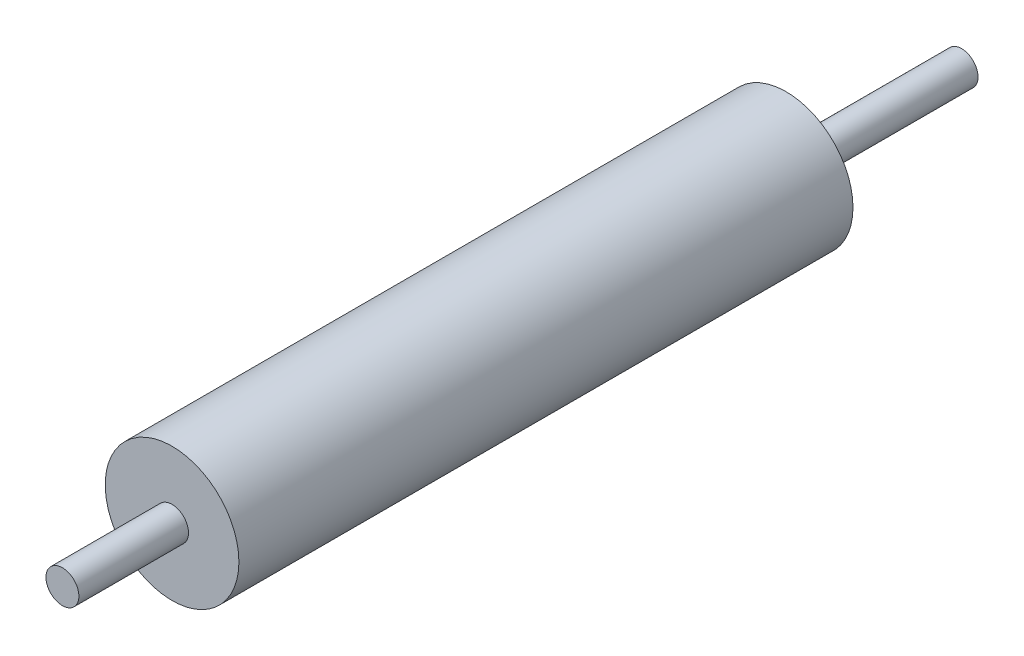
SolidWorks part; units mm, degrees
ref_plane "Front Plane" through (0, 0, 0) normal (0, 0, 1) x (1, 0, 0)
ref_plane "Top Plane" through (0, 0, 0) normal (0, 1, 0) x (1, 0, 0)
ref_plane "Right Plane" through (0, 0, 0) normal (1, 0, 0) x (0, 0, -1)
sketch "Sketch1" plane through (0, 0, 0) normal (0, 0, 1) x (1, 0, 0)
  circle A0 centre (0, 0) radius 30.48
  dimension "D1" = 60.96
extrude "Boss-Extrude1" add sketch "Sketch1" along normal blind 280
sketch "Sketch2" plane through (0, 0, 280) normal (0, 0, 1) x (1, 0, 0)
  circle A0 centre (0, 0) radius 7.5
  dimension "D1" = 15
extrude "Boss-Extrude2" add sketch "Sketch2" along normal blind 50
sketch "Sketch3" plane through (0, 0, 0) normal (0, 0, -1) x (-1, 0, 0)
  circle A0 centre (0, 0) radius 7.5
  dimension "D1" = 15
extrude "Boss-Extrude3" add sketch "Sketch3" along normal blind 80
